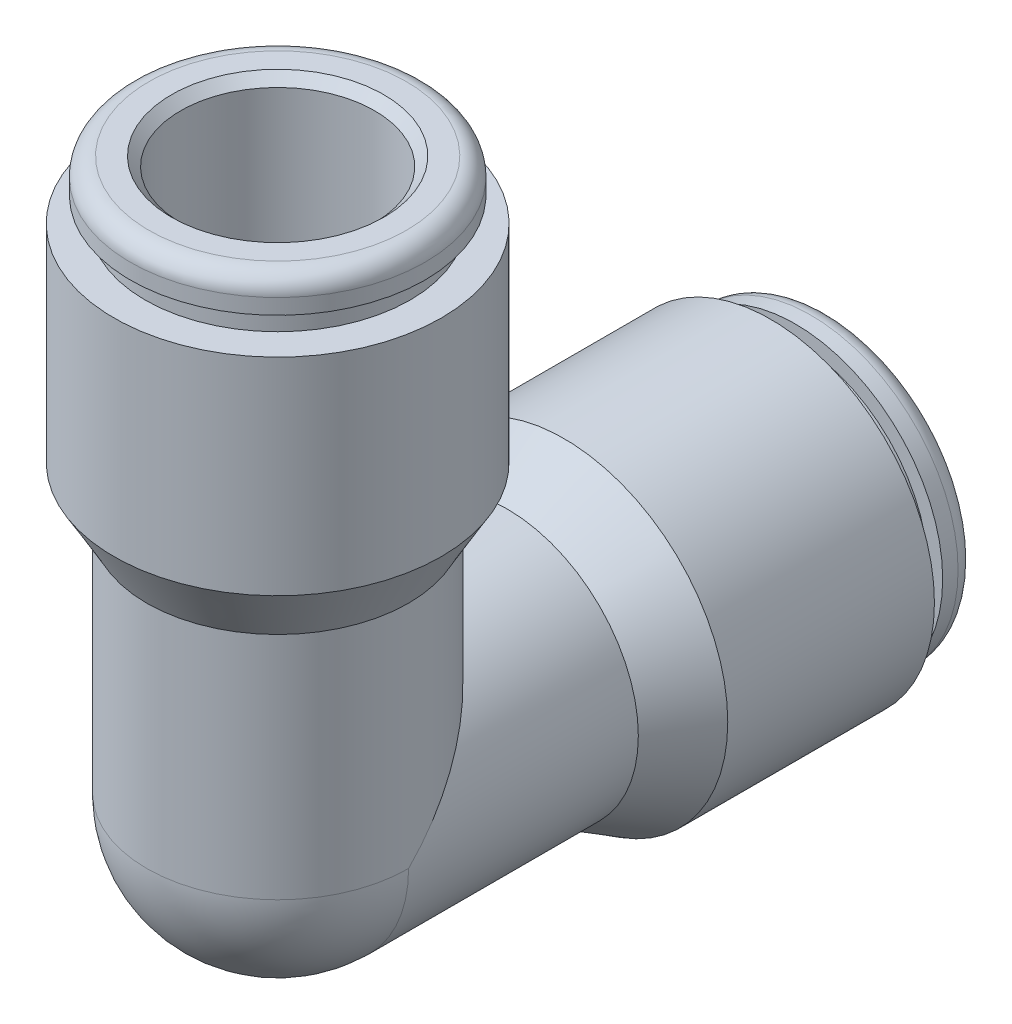
SolidWorks part; units mm, degrees
ref_plane "Front Plane" through (0, 0, 0) normal (0, 0, 1) x (1, 0, 0)
ref_plane "Top Plane" through (0, 0, 0) normal (0, 1, 0) x (1, 0, 0)
ref_plane "Right Plane" through (0, 0, 0) normal (1, 0, 0) x (0, 0, -1)
sketch "Sketch1" plane through (0, 0, 0) normal (1, 0, 0) x (0, 0, -1)
  line L0 (21.353, 6.075) -> (21.988, 6.075)
  line L1 (11.8133, 6.75) -> (20.337, 6.75)
  line L2 (0, 5.4) -> (0, 3.238)
  line L3 (8, 4) -> (22.369, 4)
  line L4 (22.75, 5.313) -> (22.75, 4.381)
  line L5 (0, 0) -> (0, 22.75) construction
  line L6 (20.337, 6.75) -> (20.337, 5.4675)
  line L7 (20.337, 5.4675) -> (21.353, 5.4675)
  line L8 (21.353, 6.075) -> (21.353, 5.4675)
  line L9 (-6.75, 22.75) -> (6.75, 22.75) construction
  line L10 (0, 0) -> (22.75, 0) construction
  line L11 (8, 4) -> (8, 3.238)
  line L12 (22.369, 4) -> (22.75, 4.381)
  line L13 (0, 0) -> (0, 3.238) construction
  line L14 (0, 5.4) -> (9.475, 5.4)
  line L15 (9.475, 5.4) -> (11.8133, 6.75)
  line L16 (8, 3.238) -> (0, 3.238)
  arc A0 (21.988, 6.075) -> (22.75, 5.313) centre (21.988, 5.313) cw
  point P1 (22.75, 4)
  point P20 (22.75, 6.075)
  dimension "D4" = 0.762
  dimension "tube od" = 8
  dimension "D1" = 1.397
  dimension "D2" = 1.016
  dimension "D3" = 10.935
  dimension "D6" = 12.15
  dimension "D9" = 30
  dimension "D10" = 10.8
  dimension "D5" = 13.275
  dimension "D8" = 13.5
  dimension "D11" = 0.762
revolve "Revolve1" add sketch "Sketch1" angle 360 about L10
ref_axis "Axis1" through (-15.8019, 0, 0) along (1, 0, 0)
pattern_circular "CirPattern1" count 2 over 90 about axis through (-15.8019, 0, 0) along (1, 0, 0) of bodies 118 123
sketch "Sketch2" plane through (0, 0, 0) normal (0, 0, 1) x (1, 0, 0)
  line L0 (-5.4, 0) -> (-3.238, 0)
  line L1 (-5.4, 0) -> (5.4, 0) construction
  line L2 (3.238, 0) -> (5.4, 0)
  arc A0 (-5.4, 0) -> (5.4, 0) centre (0, 0) ccw
  arc A2 (-3.238, 0) -> (3.238, 0) centre (0, 0) ccw
  circle A4 centre (0, 0) radius 3.238 construction
  circle A5 centre (0, 0) radius 5.4 construction
revolve "Revolve2" add sketch "Sketch2" angle 90 about L1
combine bodies "Combine1" operation type add bodies to combine 122 124
sketch "Sketch3" plane through (0, 0, 0) normal (1, 0, 0) x (0, 0, -1)
  line L0 (22.75, 4.381) -> (22.369, 4)
  line L1 (22.369, 4) -> (8, 4)
  line L2 (8, 4) -> (8, 3.238)
  line L3 (8, 3.238) -> (0, 3.238)
  line L4 (0, 3.238) -> (0, 0)
  line L5 (0, 0) -> (22.75, 0)
  line L6 (22.75, 0) -> (22.75, 4.381)
revolve "Cut-Revolve1" cut sketch "Sketch3" angle 360 about L5
pattern_circular "CirPattern2" count 2 over 90 about axis through (-15.8019, 0, 0) along (1, 0, 0) of "Cut-Revolve1"
equation "\"D6@Sketch1\" = \"G@Sketch1\"*.9"
equation "\"D3@Sketch1\" = \"D6@Sketch1\"*.9"
equation "\"D10@Sketch1\" = \"G@Sketch1\"*.8"
equation "\"D5@Sketch1\" = \"L@Sketch1\"*.45"
equation "\"D8@Sketch1\" = \"G@Sketch1\""
